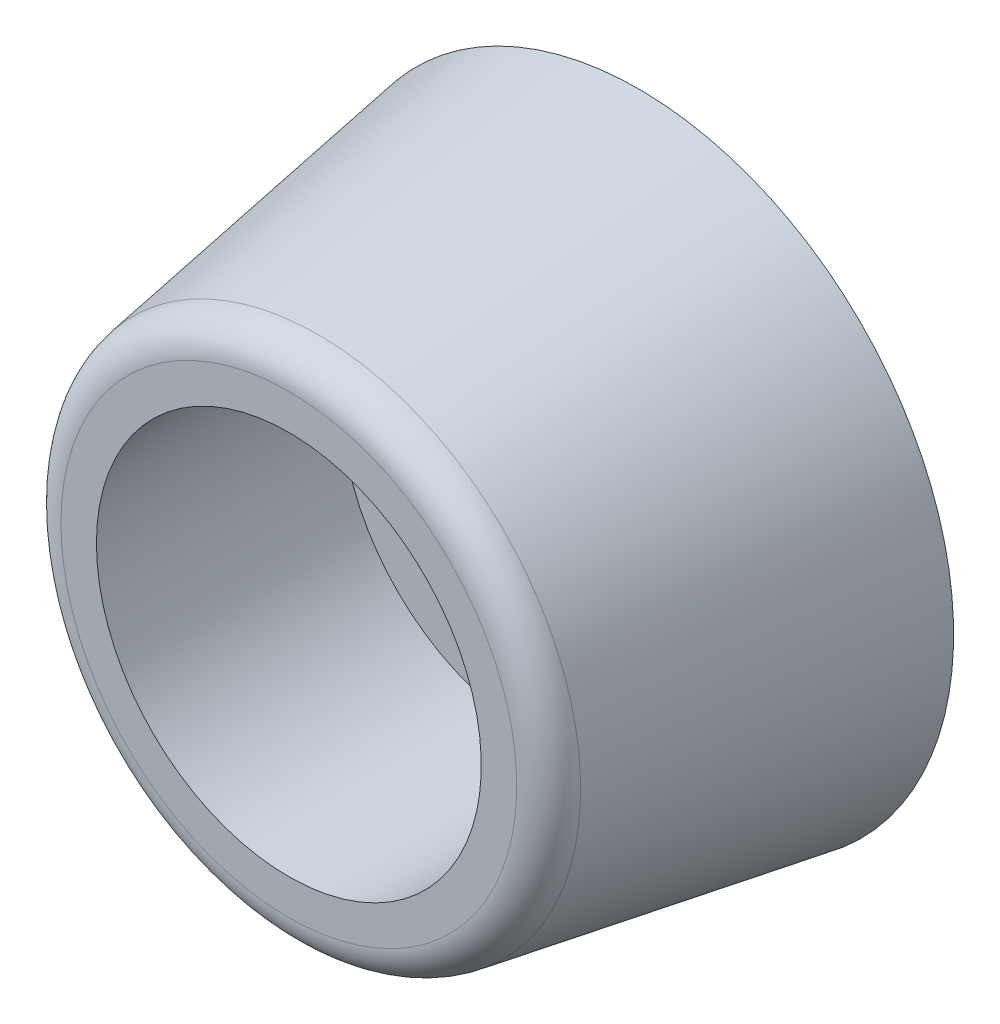
SolidWorks part; units mm, degrees
material "Бутил"
ref_plane "Front" through (0, 0, 0) normal (0, 0, 1) x (1, 0, 0)
ref_plane "Top" through (0, 0, 0) normal (0, 1, 0) x (1, 0, 0)
ref_plane "Right" through (0, 0, 0) normal (1, 0, 0) x (0, 0, -1)
sketch "Эскиз1" plane through (0, 0, 0) normal (0, 1, 0) x (1, 0, 0)
  line L0 (0, 0) -> (0, -29.287) construction
  line L1 (-2.15, 0) -> (-9, 0)
  line L2 (-9, 0) -> (-7.5, -9.1616)
  line L3 (-6.5131, -10) -> (-5.5, -10)
  line L4 (-5.5, -10) -> (-5.5, -3)
  line L5 (-5.5, -3) -> (-2.15, -3)
  line L6 (-2.15, -3) -> (-2.15, 0)
  arc A0 (-7.5, -9.1616) -> (-6.5131, -10) centre (-6.5131, -9) ccw
  point P8 (0, 0)
  point P12 (0, 0)
  point P13 (-7.5, -9.4166)
  point P14 (-6.2044, -10)
  dimension "D7" = 1
  dimension "D1" = 18
  dimension "D2" = 10
  dimension "D3" = 11
  dimension "D4" = 4.3
  dimension "D5" = 7
  dimension "D6" = 2
revolve "Повернуть1" add sketch "Эскиз1" angle 360 about L0
